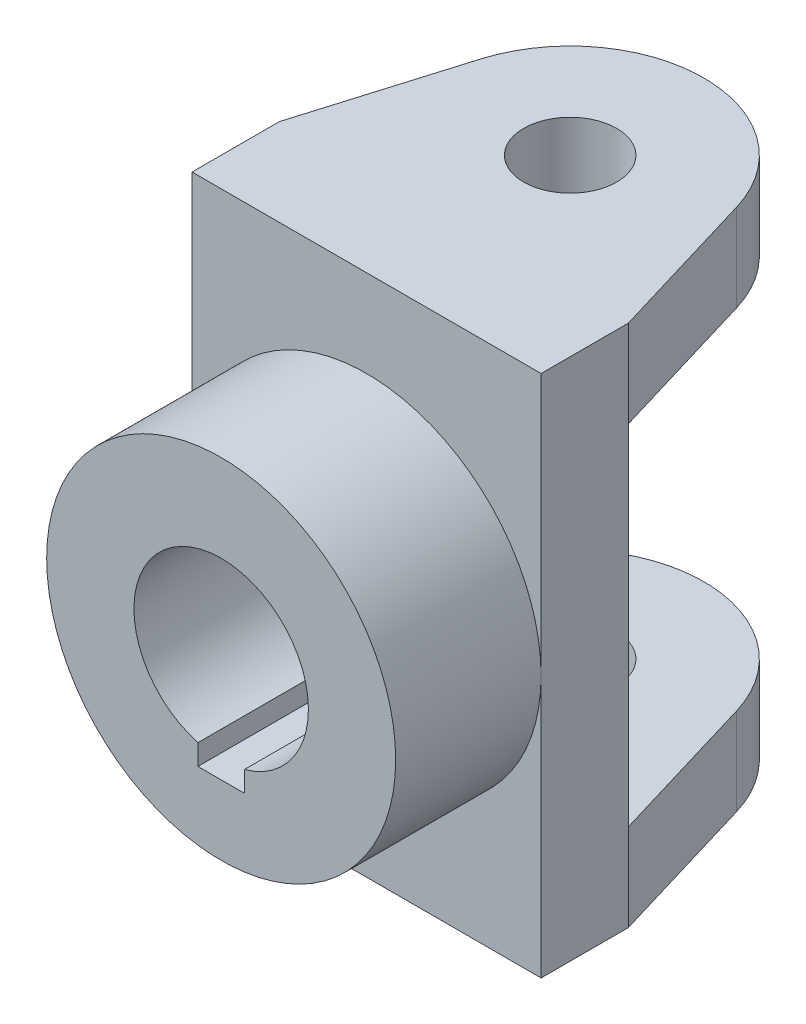
SolidWorks part; units mm, degrees
ref_plane "Front Plane" through (0, 0, 0) normal (0, 0, 1) x (1, 0, 0)
ref_plane "Top Plane" through (0, 0, 0) normal (0, 1, 0) x (1, 0, 0)
ref_plane "Right Plane" through (0, 0, 0) normal (1, 0, 0) x (0, 0, -1)
sketch "Sketch1" plane through (0, 0, 0) normal (0, 0, 1) x (1, 0, 0)
  line L1 (30, -45) -> (-30, -45)
  line L2 (30, -45) -> (30, 45)
  line L3 (30, 45) -> (-30, 45)
  line L4 (-30, -45) -> (-30, 45)
  line L5 (30, -45) -> (-30, 45) construction
  line L6 (30, 45) -> (-30, -45) construction
  point P0 (0, 0)
  dimension "D1" = 60
  dimension "D2" = 90
extrude "Boss-Extrude1" add sketch "Sketch1" along normal blind 15
sketch "Sketch2" plane through (0, 0, 15) normal (0, 0, 1) x (1, 0, 0)
  line L0 (-4, -14.4568) -> (-4, -18)
  line L3 (-4, -18) -> (4, -18)
  line L4 (4, -14.4568) -> (4, -18)
  arc A0 (4, -14.4568) -> (-4, -14.4568) centre (0, 0) ccw
  circle A1 centre (0, 0) radius 30
  dimension "D1" = 30
  dimension "D2" = 60
extrude "Boss-Extrude2" add sketch "Sketch2" along normal blind 25
sketch "Sketch3" plane through (0, 45, 0) normal (0, 1, 0) x (1, 0, 0)
  line L0 (-30, -15) -> (30, -15) construction
  line L1 (30, 0) -> (22.0329, 26.5993)
  line L2 (-30, 0) -> (-22.0329, 26.5993)
  line L3 (-30, 0) -> (30, 0)
  circle A0 centre (0, 20) radius 8
  arc A1 (22.0329, 26.5993) -> (-22.0329, 26.5993) centre (0, 20) ccw
  dimension "D1" = 46
  dimension "D2" = 16
  dimension "D3" = 35
extrude "Boss-Extrude3" add sketch "Sketch3" against normal blind 15
mirror "Mirror1" about plane through (0, 0, 0) normal (0, 1, 0) of "Boss-Extrude3"
